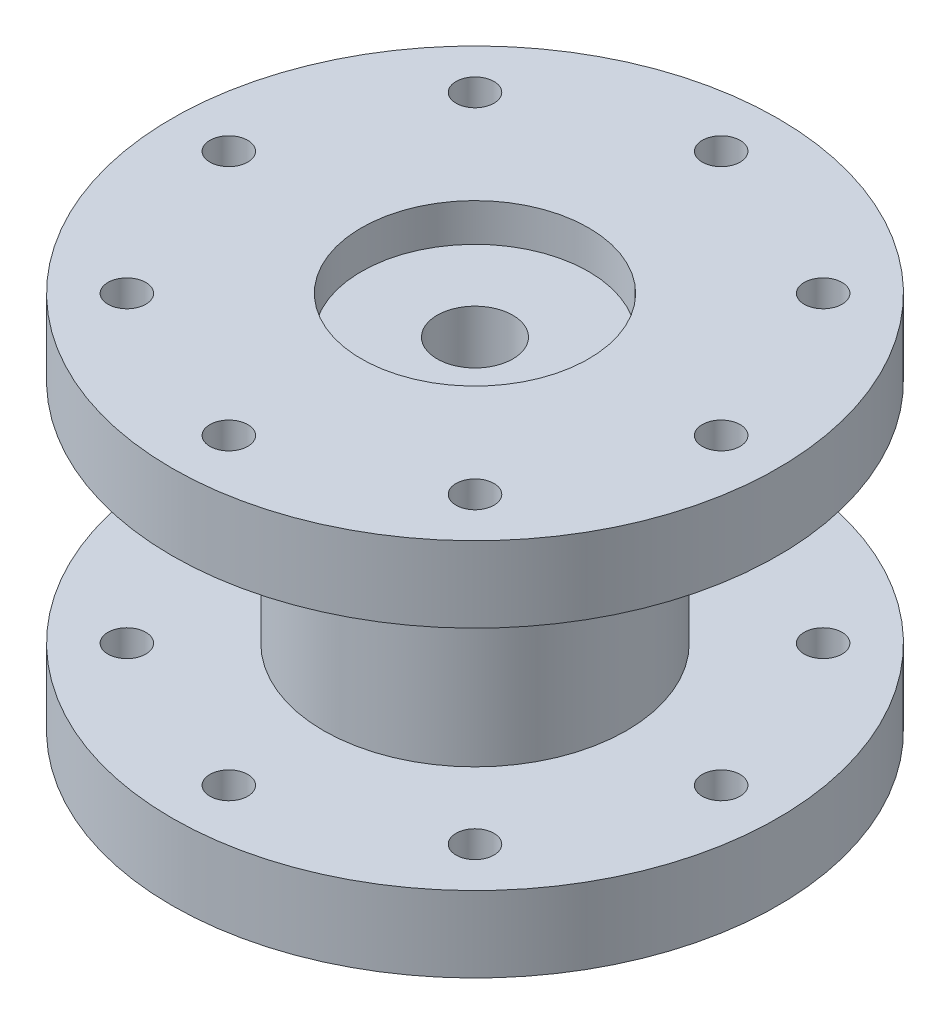
SolidWorks part; units mm, degrees
ref_plane "Front Plane" through (0, 0, 0) normal (0, 0, 1) x (1, 0, 0)
ref_plane "Top Plane" through (0, 0, 0) normal (0, 1, 0) x (1, 0, 0)
ref_plane "Right Plane" through (0, 0, 0) normal (1, 0, 0) x (0, 0, -1)
sketch "Sketch1" plane through (0, 0, 0) normal (0, 0, 1) x (1, 0, 0)
  line L0 (19.05, 0) -> (50.8, 0)
  line L1 (55.88, 0) -> (-55.88, 0) construction
  line L2 (50.8, 0) -> (50.8, 12.7)
  line L3 (50.8, 12.7) -> (25.4, 12.7)
  line L4 (25.4, 12.7) -> (25.4, 50.8)
  line L5 (25.4, 50.8) -> (50.8, 50.8)
  line L6 (50.8, 50.8) -> (50.8, 63.5)
  line L7 (50.8, 63.5) -> (19.05, 63.5)
  line L8 (19.05, 63.5) -> (19.05, 57.15)
  line L9 (19.05, 57.15) -> (6.35, 57.15)
  line L10 (6.35, 57.15) -> (6.35, 6.35)
  line L11 (6.35, 6.35) -> (19.05, 6.35)
  line L12 (19.05, 6.35) -> (19.05, 0)
  line L13 (0, 0) -> (0, 66.04) construction
  line L14 (0, -34.925) -> (0, 34.925) construction
  dimension "D1" = 63.5
  dimension "D2" = 66.04
  dimension "D3" = 12.7
  dimension "D4" = 50.8
  dimension "D5" = 6.35
  dimension "D6" = 25.4
  dimension "D7" = 19.05
  dimension "D8" = 6.35
  dimension "D9" = 50.8
revolve "Revolve2" add sketch "Sketch1" angle 360 about L13
sketch "Sketch2" plane through (0, 63.5, 0) normal (0, 1, 0) x (1, 0, 0)
  line L0 (0, 0) -> (41.275, 0) construction
  circle A0 centre (0, 0) radius 41.275 construction
  circle A1 centre (41.275, 0) radius 3.175
  circle A2 centre (29.1858, -29.1858) radius 3.175
  circle A3 centre (0, -41.275) radius 3.175
  circle A4 centre (-29.1858, -29.1858) radius 3.175
  circle A5 centre (-41.275, 0) radius 3.175
  circle A6 centre (-29.1858, 29.1858) radius 3.175
  circle A7 centre (0, 41.275) radius 3.175
  circle A8 centre (29.1858, 29.1858) radius 3.175
  dimension "D1" = 82.55
  dimension "D2" = 6.35
  dimension "D4" = 41.275
  dimension "D3" = 8
extrude "Cut-Extrude1" cut sketch "Sketch2" against normal through all
